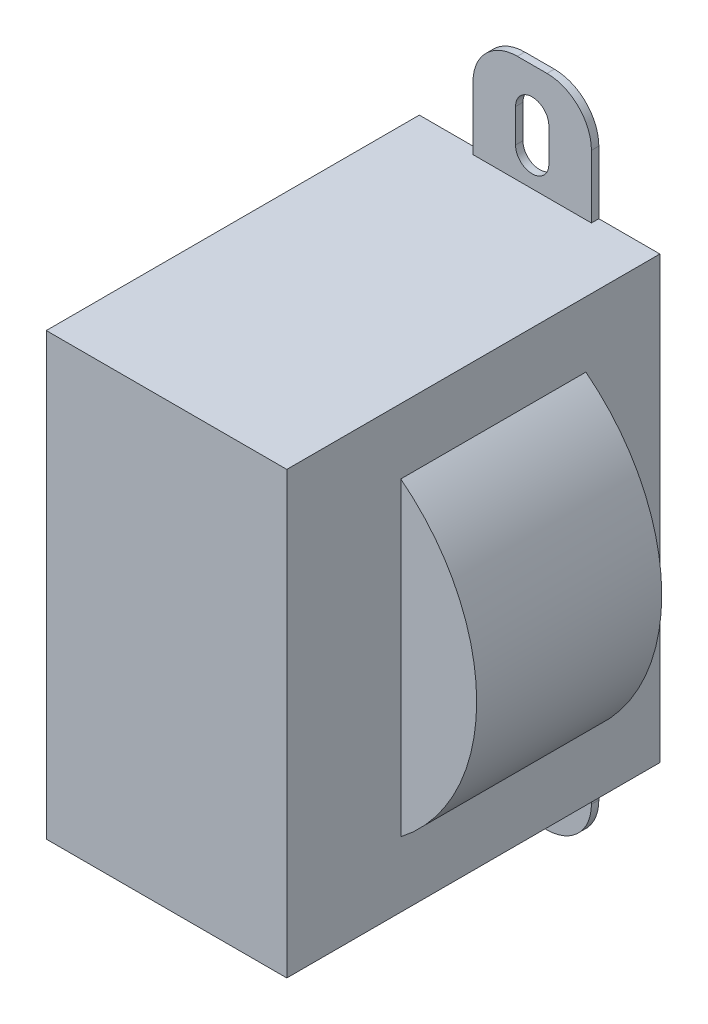
SolidWorks part; units mm, degrees
ref_plane "前视基准面" through (0, 0, 0) normal (0, 0, 1) x (1, 0, 0)
ref_plane "上视基准面" through (0, 0, 0) normal (0, 1, 0) x (1, 0, 0)
ref_plane "右视基准面" through (0, 0, 0) normal (1, 0, 0) x (0, 0, -1)
sketch "草图1" plane through (0, 0, 0) normal (0, 0, 1) x (1, 0, 0)
  line L0 (0, 107.8945) -> (0, -117.3589) construction
  line L1 (-16.25, 29.75) -> (16.25, 29.75)
  line L2 (-16.25, 29.75) -> (-16.25, -29.75)
  line L3 (-16.25, -29.75) -> (16.25, -29.75)
  line L4 (16.25, 29.75) -> (16.25, -29.75)
  line L5 (-105.0552, 0) -> (107.8945, 0) construction
  dimension "D1" = 32.5
  dimension "D2" = 59.5
extrude "拉伸1" add sketch "草图1" along normal blind 42.4
ref_plane "基准面1" through (0, 0, 10) normal (0, 0, 1) x (1, 0, 0)
sketch "草图2" plane through (0, 0, 10) normal (0, 0, 1) x (1, 0, 0)
  line L0 (-16.25, 20.9329) -> (16.25, 20.9329)
  line L1 (-16.25, 29.75) -> (-16.25, -29.75) construction
  line L2 (16.25, -29.75) -> (16.25, 29.75) construction
  line L3 (16.25, -20.9329) -> (-16.25, -20.9329)
  arc A0 (-16.25, 20.9329) -> (-16.25, -20.9329) centre (0, 0) ccw
  arc A1 (16.25, -20.9329) -> (16.25, 20.9329) centre (0, 0) ccw
  dimension "D1" = 26.5
extrude "拉伸2" add sketch "草图2" along normal blind 25
sketch "草图4" plane through (0, 0, 0) normal (0, 0, 1) x (1, 0, 0)
  line L0 (0, 48.5161) -> (0, -34.8903) construction
  line L1 (16.25, 29.75) -> (-16.25, 29.75) construction
  line L2 (-2, 44.25) -> (2, 44.25)
  line L3 (-8, 38.25) -> (-8, 29.75)
  line L4 (-8, 29.75) -> (8, 29.75)
  line L5 (8, 38.25) -> (8, 29.75)
  line L6 (-32.7557, 0) -> (34.5425, 0) construction
  line L7 (-2, -44.25) -> (2, -44.25)
  line L8 (-8, -38.25) -> (-8, -29.75)
  line L9 (-8, -29.75) -> (8, -29.75)
  line L10 (8, -38.25) -> (8, -29.75)
  line L11 (-2.25, 38.25) -> (-2.25, 33.75)
  line L12 (2.25, 38.25) -> (2.25, 33.75)
  line L13 (2.25, -38.25) -> (2.25, -33.75)
  line L14 (-2.25, -38.25) -> (-2.25, -33.75)
  arc A0 (-2.25, 33.75) -> (2.25, 33.75) centre (0, 33.75) ccw
  arc A1 (2.25, -38.25) -> (-2.25, -38.25) centre (0, -38.25) cw
  arc A2 (2.25, 38.25) -> (-2.25, 38.25) centre (0, 38.25) ccw
  arc A3 (-2.25, -33.75) -> (2.25, -33.75) centre (0, -33.75) cw
  arc A4 (8, 38.25) -> (2, 44.25) centre (2, 38.25) ccw
  arc A5 (-8, 38.25) -> (-2, 44.25) centre (-2, 38.25) cw
  arc A6 (8, -38.25) -> (2, -44.25) centre (2, -38.25) cw
  arc A7 (-8, -38.25) -> (-2, -44.25) centre (-2, -38.25) ccw
  point P29 (8, 44.25)
  point P32 (-8, 44.25)
  dimension "D4" = 4.5
  dimension "D5" = 4.5
  dimension "D6" = 6
  dimension "D7" = 6
  dimension "D1" = 14.5
  dimension "D2" = 16
  dimension "D3" = 67.5
extrude "拉伸3" add sketch "草图4" along normal blind 1
sketch "草图5" plane through (0, 0, 42.4) normal (0, 0, 1) x (1, 0, 0)
  line L0 (-16.25, -29.75) -> (16.25, -29.75) construction
  line L1 (16.25, 29.75) -> (-16.2432, 29.75)
  line L2 (16.25, 29.75) -> (16.25, -29.75)
  line L3 (16.25, -29.75) -> (-16.2432, -29.75)
  line L4 (-16.2432, 29.75) -> (-16.2432, -29.75)
extrude "拉伸5" add sketch "草图5" along normal blind 8
